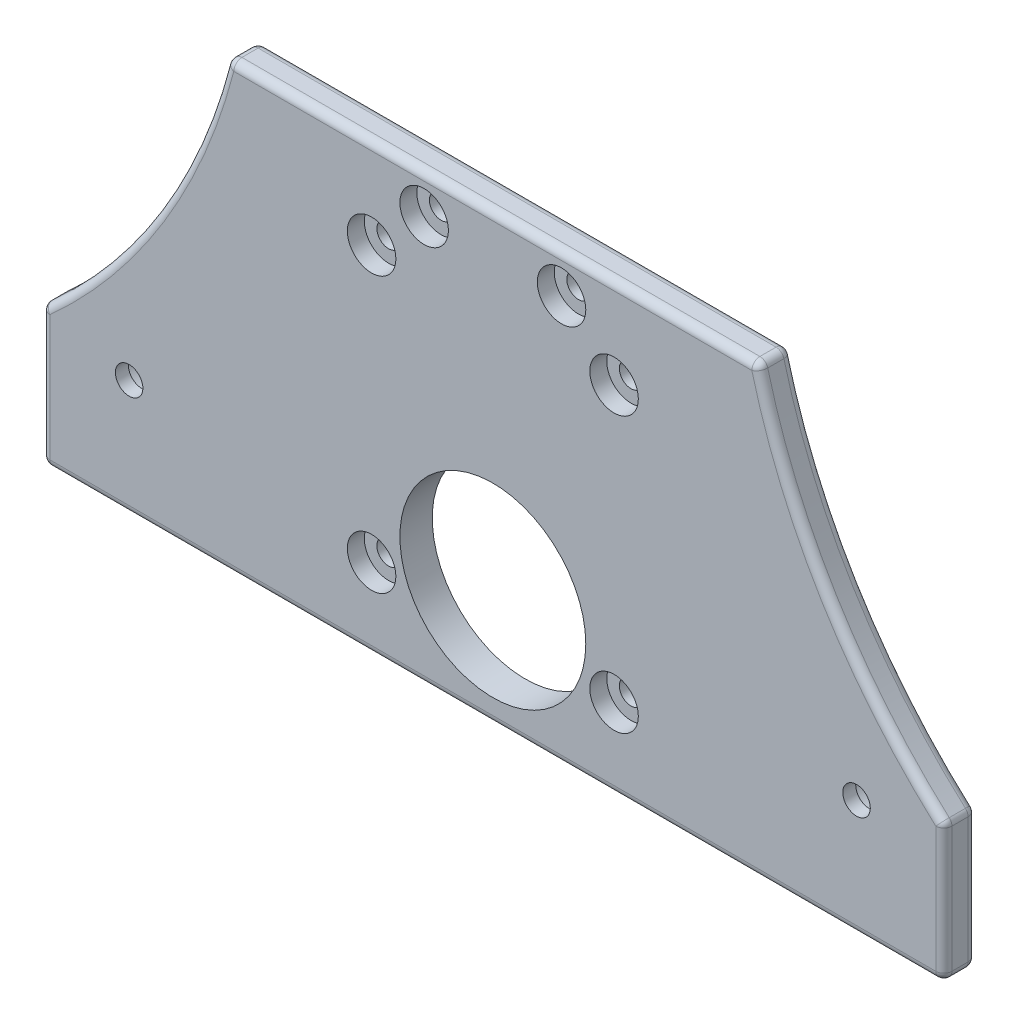
SolidWorks part; units mm, degrees
ref_plane "Plan de face" through (0, 0, 0) normal (0, 0, 1) x (1, 0, 0)
ref_plane "Plan de dessus" through (0, 0, 0) normal (0, 1, 0) x (1, 0, 0)
ref_plane "Plan de droite" through (0, 0, 0) normal (1, 0, 0) x (0, 0, -1)
sketch "Esquisse1" plane through (0, 0, 0) normal (0, 0, 1) x (1, 0, 0)
  line L0 (0, 0) -> (0, 43.5023) construction
  line L5 (4.7602, 28.5895) -> (15, 28.5895) construction
  line L6 (4.7602, 28.5895) -> (4.7602, -5.4105) construction
  line L7 (4.7602, -5.4105) -> (15, -5.4105) construction
  line L8 (15, 28.5895) -> (15, -5.4105) construction
  line L9 (4.5433, 19.9594) -> (45, 19.9594) construction
  line L10 (4.5433, 19.9594) -> (4.5433, -5.4105) construction
  line L12 (45, 19.9594) -> (45, -5.4105) construction
  line L14 (55.8018, -15.33) -> (-55.8018, -15.33)
  line L16 (-32.822, 39.67) -> (32.822, 39.67)
  line L17 (55.8018, -15.33) -> (55.8018, 1.67)
  line L18 (-55.8018, -15.33) -> (-55.8018, 1.67)
  line L19 (-15, -5.4105) -> (15, -5.4105) construction
  line L20 (0, -0.9105) -> (45, -0.9105) construction
  circle A0 centre (15, -5.4105) radius 1.2
  circle A1 centre (15, 28.5895) radius 1.2
  circle A4 centre (-15, -5.4105) radius 1.2
  circle A5 centre (-15, 28.5895) radius 1.2
  circle A6 centre (0, -0.9105) radius 11.5
  arc A7 (32.822, 39.67) -> (55.8018, 1.67) centre (105.7607, 57.83) ccw
  arc A8 (-32.822, 39.67) -> (-55.8018, 1.67) centre (-105.7607, 57.83) cw
  circle A9 centre (45, -0.9105) radius 1
  circle A10 centre (-45, -0.9105) radius 1
  circle A11 centre (-8.5, 34.8895) radius 1
  circle A12 centre (8.5, 34.8895) radius 1
  point P34 (0, 0)
  dimension "D1" = 23
  dimension "D2" = 2.4
  dimension "D11" = 2
  dimension "D14" = 2
  dimension "D3" = 30
  dimension "D4" = 4.5
  dimension "D5" = 34
  dimension "D6" = 90
  dimension "D7" = 15.33
  dimension "D8" = 17
  dimension "D9" = 14.4195
  dimension "D10" = 55
  dimension "D12" = 17
  dimension "D13" = 35.8
extrude "Boss.-Extru.1" add sketch "Esquisse1" along normal blind 4
hole_wizard "Chambrage pour vis à tête ronde bombée M2.51" positions "Esquisse7" profile "Esquisse8" counterbore size "M2.5" standard "Ansi Metric" end condition through all
sketch "Esquisse7" plane through (0, 0, 4) normal (0, 0, 1) x (1, 0, 0)
  point P0 (-15, 28.5895)
  point P3 (15, 28.5895)
  point P6 (15, -5.4105)
  point P9 (-15, -5.4105)
sketch "Esquisse8" plane through (-15, 28.5895, 4) normal (1, 0, 0) x (0, -1, 0)
  line L0 (0, 0) -> (0, 4)
  line L1 (0, 4) -> (1.45, 4)
  line L3 (1.45, 4) -> (1.45, 2.1)
  line L4 (1.45, 2.1) -> (3, 2.1)
  line L5 (3, 2.1) -> (3, 0)
  line L7 (3, 0) -> (0, 0)
  line L11 (0, -6.35) -> (0, 107.95) construction
  dimension "Diamètre du perçage jusqu'au prochain" = 2.9
  dimension "Profondeur du perçage jusqu'au prochain" = 4
  dimension "Diamètre du chambrage" = 6
  dimension "Profondeur du chambrage" = 2.1
fillet "Congé1" radius 1 18 edges at (-55.8018, -6.83, 4) (-55.8018, -6.83, 0) (-55.8018, -15.33, 2) (0, -15.33, 4) (0, -15.33, 0) (55.8018, -15.33, 2) (55.8018, -6.83, 4) (55.8018, -6.83, 0) (55.8018, 1.67, 2) (41.4416, 18.9342, 4) (41.4416, 18.9342, 0) (32.822, 39.67, 2) (0, 39.67, 4) (0, 39.67, 0) (-32.822, 39.67, 2) (-41.4416, 18.9342, 4) (-55.8018, 1.67, 2) (-41.4416, 18.9342, 0)
hole_wizard "Dégagement M34" positions "Esquisse12" profile "Esquisse13" hole size "M3" standard "Ansi Metric" end condition through all
sketch "Esquisse12" plane through (0, 0, 4) normal (0, 0, 1) x (1, 0, 0)
  point P0 (-45, -0.9105)
  point P3 (45, -0.9105)
sketch "Esquisse13" plane through (-45, -0.9105, 4) normal (1, 0, 0) x (0, -1, 0)
  line L0 (0, 0) -> (0, 4)
  line L1 (0, 4) -> (1.7, 4)
  line L2 (1.7, 4) -> (1.7, 0)
  line L5 (1.7, 0) -> (0, 0)
  line L11 (0, -6.35) -> (0, 107.95) construction
  dimension "Diamètre du perçage jusqu'au prochain" = 3.4
  dimension "Profondeur du perçage jusqu'au prochain" = 4
hole_wizard "Chambrage pour vis à tête ronde bombée M2.52" positions "Esquisse14" profile "Esquisse15" counterbore size "M2.5" standard "Ansi Metric" end condition through all
sketch "Esquisse14" plane through (0, 0, 4) normal (0, 0, 1) x (1, 0, 0)
  point P0 (-8.5, 34.8895)
  point P3 (8.5, 34.8895)
sketch "Esquisse15" plane through (-8.5, 34.8895, 4) normal (1, 0, 0) x (0, -1, 0)
  line L0 (0, 0) -> (0, 4)
  line L1 (0, 4) -> (1.45, 4)
  line L3 (1.45, 4) -> (1.45, 2.1)
  line L4 (1.45, 2.1) -> (3, 2.1)
  line L5 (3, 2.1) -> (3, 0)
  line L7 (3, 0) -> (0, 0)
  line L11 (0, -6.35) -> (0, 107.95) construction
  dimension "Diamètre du perçage jusqu'au prochain" = 2.9
  dimension "Profondeur du perçage jusqu'au prochain" = 4
  dimension "Diamètre du chambrage" = 6
  dimension "Profondeur du chambrage" = 2.1
hole_wizard "Chambrage pour vis à tête ronde bombée M31" positions "Esquisse16" profile "Esquisse17" counterbore size "M3" standard "Ansi Metric" end condition through all
sketch "Esquisse16" plane through (0, 0, 0) normal (0, 0, -1) x (-1, 0, 0)
  point P0 (45, -0.9105)
  point P3 (-45, -0.9105)
sketch "Esquisse17" plane through (-45, -0.9105, 0) normal (1, 0, 0) x (0, 1, 0)
  line L0 (0, 0) -> (0, 4)
  line L1 (0, 4) -> (1.7, 4)
  line L3 (1.7, 4) -> (1.7, 2.4)
  line L4 (1.7, 2.4) -> (3.5, 2.4)
  line L5 (3.5, 2.4) -> (3.5, 0)
  line L7 (3.5, 0) -> (0, 0)
  line L11 (0, -6.35) -> (0, 107.95) construction
  dimension "Diamètre du perçage jusqu'au prochain" = 3.4
  dimension "Profondeur du perçage jusqu'au prochain" = 4
  dimension "Diamètre du chambrage" = 7
  dimension "Profondeur du chambrage" = 2.4
